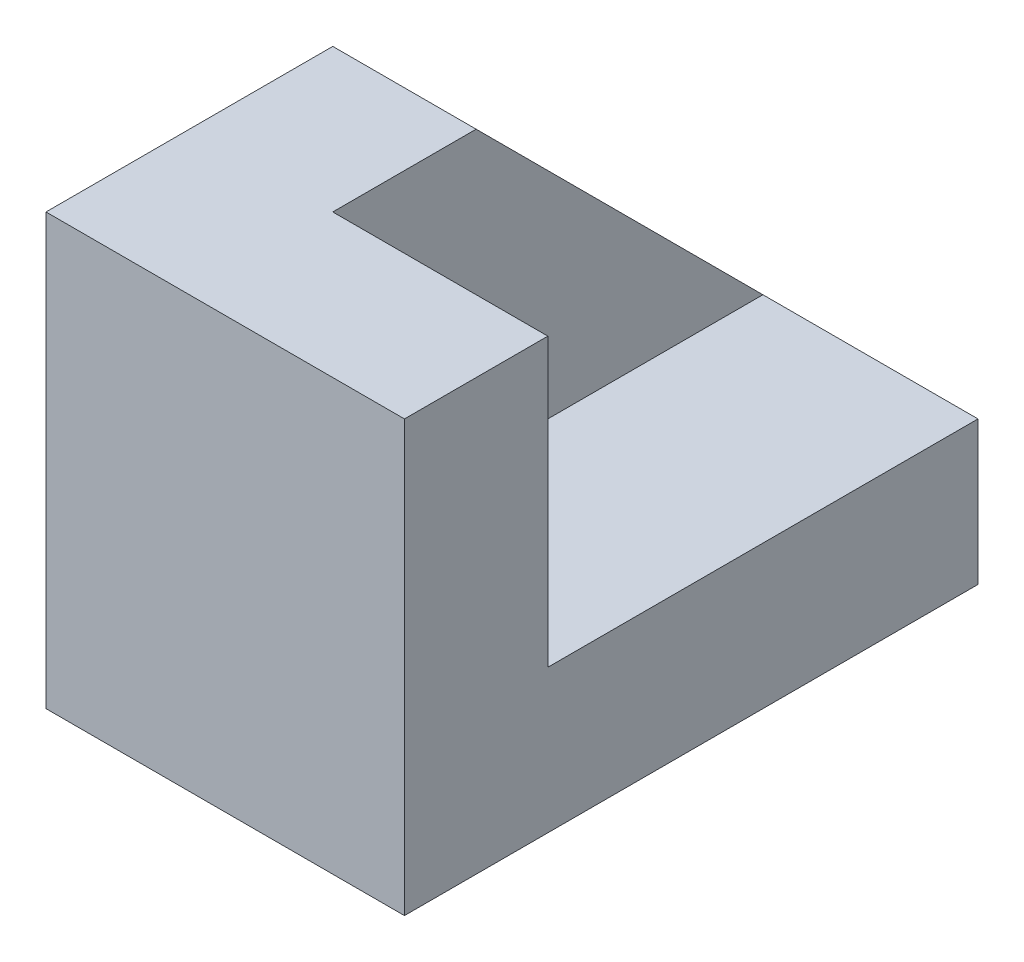
SolidWorks part; units mm, degrees
ref_plane "Alzado" through (0, 0, 0) normal (0, 0, 1) x (1, 0, 0)
ref_plane "Planta" through (0, 0, 0) normal (0, 1, 0) x (1, 0, 0)
ref_plane "Vista lateral" through (0, 0, 0) normal (1, 0, 0) x (0, 0, -1)
sketch "Croquis2" plane through (0, 0, 0) normal (1, 0, 0) x (0, 0, -1)
  line L0 (0, 3) -> (4, -1)
  line L1 (-4, -3) -> (4, -3)
  line L2 (-4, -3) -> (-4, 3)
  line L3 (-4, 3) -> (0, 3)
  line L4 (4, -3) -> (4, -1)
  line L5 (-4, -3) -> (4, 3) construction
  line L6 (-4, 3) -> (4, -3) construction
  point P0 (0, 0)
  dimension "D1" = 8
  dimension "D2" = 6
extrude "Saliente-Extruir2" add sketch "Croquis2" along normal blind 5
sketch "Croquis4" plane through (0, 3, 0) normal (0, 1, 0) x (1, 0, 0)
  line L0 (5, 0) -> (5, -4) construction
  line L1 (5, -2) -> (2, -2)
  line L2 (5, -2) -> (5, 4)
  line L3 (5, 4) -> (2, 4)
  line L4 (2, -2) -> (2, 4)
  line L5 (5, 4) -> (0, 4) construction
  dimension "D1" = 3
  dimension "D2" = 6
extrude "Cortar-Extruir1" cut sketch "Croquis4" against normal blind 4
sketch "Croquis5" plane through (0, 1.5, -1.5) normal (0, 0.7071, -0.7071) x (1, 0, 0)
  line L0 (1.2894, -1.6042) -> (1.2894, 2.9434) construction
  text T0 "SOLIDWORKS 2026\r\n" font "Century Gothic" height 0.35
